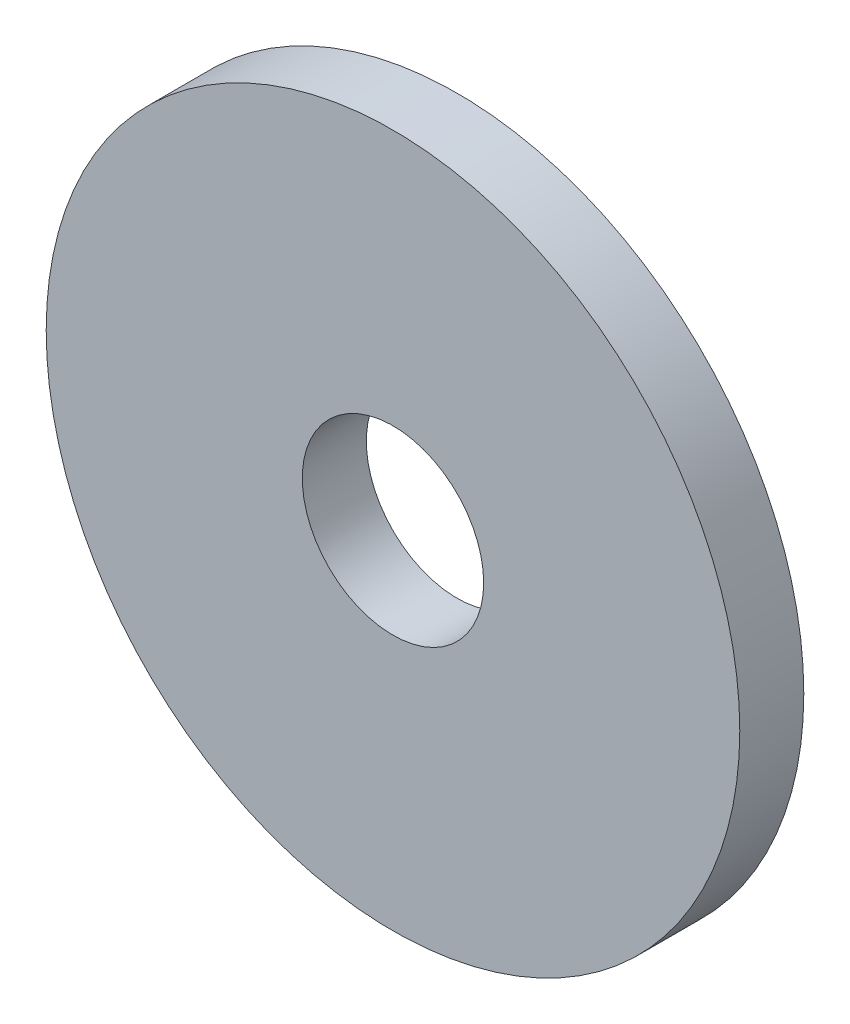
SolidWorks part; units mm, degrees
ref_plane "前视基准面" through (0, 0, 0) normal (0, 0, 1) x (1, 0, 0)
ref_plane "上视基准面" through (0, 0, 0) normal (0, 1, 0) x (1, 0, 0)
ref_plane "右视基准面" through (0, 0, 0) normal (1, 0, 0) x (0, 0, -1)
sketch "草图1" plane through (0, 0, 0) normal (0, 0, 1) x (1, 0, 0)
  circle A0 centre (0, 0) radius 8.5
  circle A1 centre (0, 0) radius 32.5
  dimension "D1" = 65
  dimension "D2" = 17
extrude "凸台-拉伸1" add sketch "草图1" along normal blind 6
